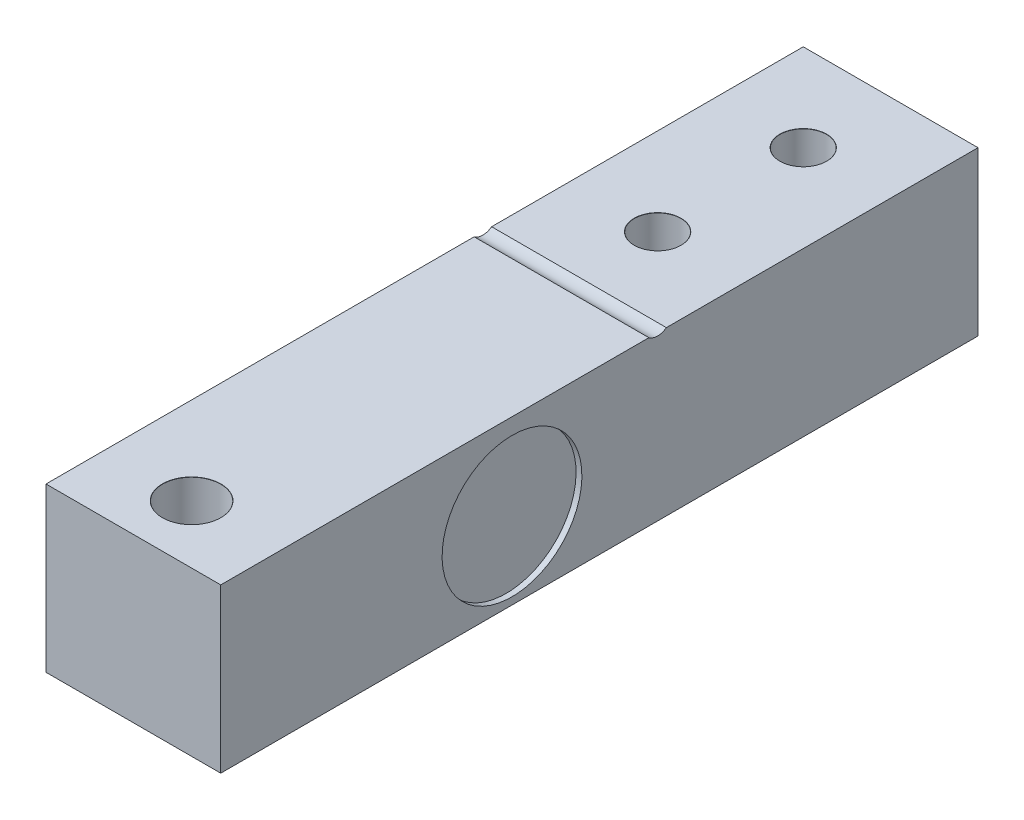
SolidWorks part; units mm, degrees
ref_plane "前视基准面" through (0, 0, 0) normal (0, 0, 1) x (1, 0, 0)
ref_plane "上视基准面" through (0, 0, 0) normal (0, 1, 0) x (1, 0, 0)
ref_plane "右视基准面" through (0, 0, 0) normal (1, 0, 0) x (0, 0, -1)
other "Configuration Table"
sketch "草图1" plane through (0, 0, 0) normal (0, 0, 1) x (1, 0, 0)
  line L1 (-15, 14) -> (15, 14)
  line L2 (-15, 14) -> (-15, -14)
  line L3 (-15, -14) -> (15, -14)
  line L4 (15, 14) -> (15, -14)
  line L5 (-15, 14) -> (15, -14) construction
  line L6 (-15, -14) -> (15, 14) construction
  point P0 (0, 0)
  dimension "D1" = 28
  dimension "D2" = 30
extrude "凸台-拉伸1" add sketch "草图1" along normal mid plane 130
sketch "草图2" plane through (-15, 0, 0) normal (-1, 0, 0) x (0, 0, 1)
  line L0 (-65, 14) -> (-65, -14) construction
  line L1 (65, 14) -> (-65, 14) construction
  circle A0 centre (-10, 16) radius 2.5
  dimension "D1" = 55
  dimension "D2" = 5
  dimension "D3" = 2
extrude "切除-拉伸1" cut sketch "草图2" against normal through all
hole_wizard "Ø8.0 (8) 直径孔1" positions "草图3" profile "草图4" hole size "Ø8.0" standard "GB" end condition through all
sketch "草图3" plane through (0, 14, 0) normal (0, 1, 0) x (1, 0, 0)
  line L0 (15, 65) -> (-15, 65) construction
  point P0 (0, 25)
  point P2 (0, 50)
  dimension "D1" = 40
  dimension "D2" = 15
sketch "草图4" plane through (0, 14, -25) normal (1, 0, 0) x (0, 0, 1)
  line L0 (0, 0) -> (0, 28)
  line L1 (0, 28) -> (4, 28)
  line L2 (4, 28) -> (4, 0.025)
  line L3 (4, 0.025) -> (4.025, 0)
  line L5 (4.025, 0) -> (0, 0)
  line L6 (-4, 0.025) -> (-4.025, 0) construction
  line L11 (0, -6.35) -> (0, 107.95) construction
  dimension "通孔孔直径" = 8
  dimension "通孔孔深度" = 28
  dimension "近端锥形沉头孔直径" = 8.05
  dimension "近端锥形沉头孔角度" = 90
hole_wizard "Ø10.0 (10) 直径孔1" positions "草图5" profile "草图6" hole size "Ø10.0" standard "GB" end condition through all
sketch "草图5" plane through (0, 14, 0) normal (0, 1, 0) x (1, 0, 0)
  line L0 (15, 65) -> (-15, 65) construction
  point P0 (0, -55)
  point P7 (0, 65)
  dimension "D1" = 120
sketch "草图6" plane through (0, 14, 55) normal (1, 0, 0) x (0, 0, 1)
  line L0 (0, 0) -> (0, 28)
  line L1 (0, 28) -> (5, 28)
  line L2 (5, 28) -> (5, 0.025)
  line L3 (5, 0.025) -> (5.025, 0)
  line L5 (5.025, 0) -> (0, 0)
  line L6 (-5, 0.025) -> (-5.025, 0) construction
  line L11 (0, -6.35) -> (0, 107.95) construction
  dimension "通孔孔直径" = 10
  dimension "通孔孔深度" = 28
  dimension "近端锥形沉头孔直径" = 10.05
  dimension "近端锥形沉头孔角度" = 90
sketch "草图7" plane through (-15, 0, 0) normal (-1, 0, 0) x (0, 0, 1)
  line L0 (-65, 14) -> (-65, -14) construction
  circle A0 centre (15, 0) radius 12
  dimension "D1" = 80
extrude "切除-拉伸2" cut sketch "草图7" against normal blind 1 contours A0
sketch "草图9" plane through (15, 0, 0) normal (1, 0, 0) x (0, 0, -1)
  line L0 (65, -14) -> (65, 14) construction
  circle A0 centre (-15, -0.777) radius 12
  dimension "D1" = 80
extrude "切除-拉伸3" cut sketch "草图9" against normal blind 1
